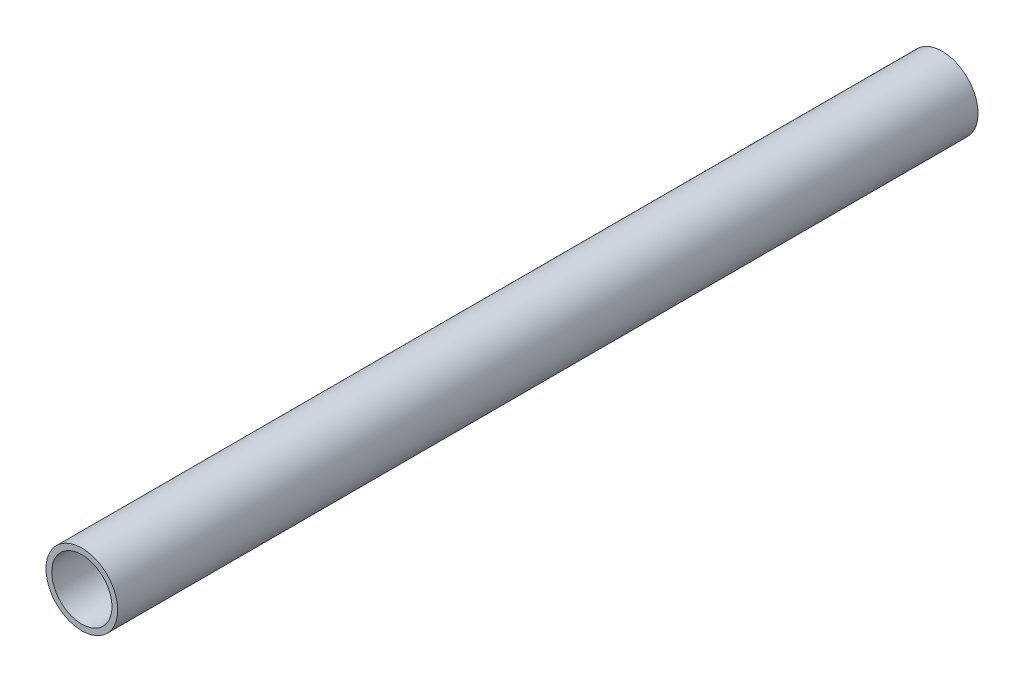
SolidWorks part; units mm, degrees
ref_plane "Front Plane" through (0, 0, 0) normal (0, 0, 1) x (1, 0, 0)
ref_plane "Top Plane" through (0, 0, 0) normal (0, 1, 0) x (1, 0, 0)
ref_plane "Right Plane" through (0, 0, 0) normal (1, 0, 0) x (0, 0, -1)
sketch "Sketch1" plane through (0, 0, 0) normal (0, 0, 1) x (1, 0, 0)
  circle A0 centre (0, 0) radius 12.7
  circle A1 centre (0, 0) radius 10.668
  dimension "D1" = 25.4
  dimension "D2" = 2.032
extrude "Boss-Extrude1" add sketch "Sketch1" along normal blind 304.8
